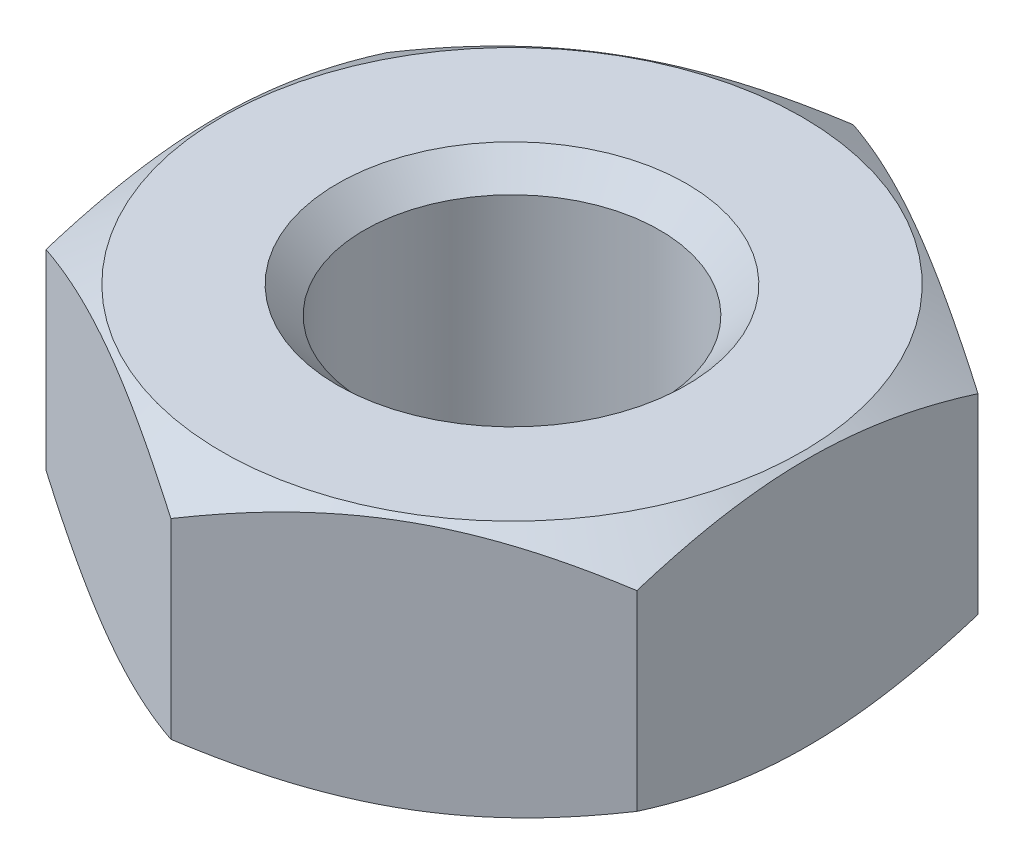
SolidWorks part; units mm, degrees
ref_plane "Front Plane" through (0, 0, 0) normal (0, 0, 1) x (1, 0, 0)
ref_plane "Top Plane" through (0, 0, 0) normal (0, 1, 0) x (1, 0, 0)
ref_plane "Right Plane" through (0, 0, 0) normal (1, 0, 0) x (0, 0, -1)
sketch "Sketch1" plane through (0, 0, 0) normal (0, 1, 0) x (1, 0, 0)
  line L1 (0, 3.1754) -> (-2.75, 1.5877)
  line L2 (-2.75, 1.5877) -> (-2.75, -1.5877)
  line L3 (-2.75, -1.5877) -> (0, -3.1754)
  line L4 (0, -3.1754) -> (2.75, -1.5877)
  line L5 (2.75, -1.5877) -> (2.75, 1.5877)
  line L6 (2.75, 1.5877) -> (0, 3.1754)
  circle A0 centre (0, 0) radius 2.75 construction
  circle A1 centre (0, 0) radius 1.375
  dimension "D1" = 2.75
  dimension "D2" = 5.5
extrude "Boss-Extrude1" add sketch "Sketch1" along normal mid plane 2.38
sketch "Sketch2" plane through (0, 0, 0) normal (1, 0, 0) x (0, 0, -1)
  line L0 (2.7, 1.19) -> (3.1754, 0.89)
  line L1 (1.5877, 1.19) -> (3.1754, 1.19) construction
  line L2 (3.1754, 1.19) -> (3.1754, -1.19) construction
  line L3 (3.1754, 0.89) -> (3.1754, 1.19)
  line L4 (3.1754, 1.19) -> (2.7, 1.19)
  line L5 (0, 0) -> (0, 1.19) construction
  line L6 (-1.5877, 1.19) -> (1.5877, 1.19) construction
  dimension "D1" = 0.3
  dimension "D2" = 2.7
revolve "Cut-Revolve1" cut sketch "Sketch2" angle 360 about L5
mirror "Mirror1" about plane through (0, 0, 0) normal (0, 1, 0) of "Cut-Revolve1"
chamfer "Chamfer1" distance 0.25 angle 45 2 edges at (0, -1.19, 1.375) (0, 1.19, 1.375)
equation "\"NutSize\"=5.5"
equation "\"D2@Sketch1\"=\"NutSize\""
equation "\"HoleSize\"=2.75"
equation "\"D1@Sketch1\"=\"HoleSize\""
equation "\"NutThickness\"=2.38"
equation "\"D1@Boss-Extrude1\"=\"NutThickness\""
equation "\"HoleChamfer\"=0.25"
equation "\"D1@Chamfer1\"=\"HoleChamfer\""
